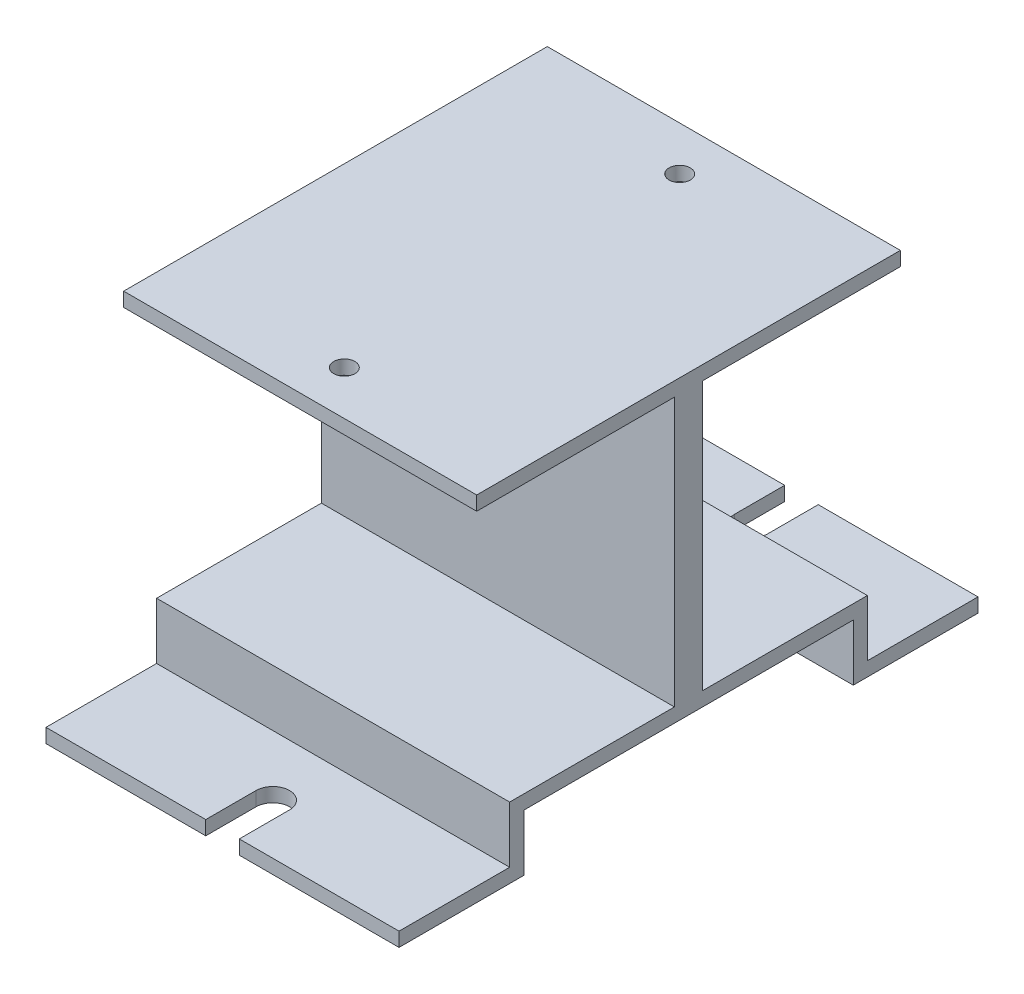
SolidWorks part; units mm, degrees
ref_plane "Front Plane" through (0, 0, 0) normal (0, 0, 1) x (1, 0, 0)
ref_plane "Top Plane" through (0, 0, 0) normal (0, 1, 0) x (1, 0, 0)
ref_plane "Right Plane" through (0, 0, 0) normal (1, 0, 0) x (0, 0, -1)
sketch "Sketch1" plane through (0, 0, 0) normal (1, 0, 0) x (0, 0, -1)
  line L0 (0, 0) -> (0, 42) construction
  line L1 (0, 0) -> (23.3335, 0)
  line L2 (23.3335, 0) -> (23.3335, -8)
  line L3 (23.3335, -8) -> (41, -8)
  line L4 (0, 42) -> (30, 42) construction
  line L5 (0, 42) -> (0, 36.5563) construction
  dimension "D1" = 60
  dimension "D2" = 50
  dimension "D3" = 82
  dimension "D4" = 8
extrude "Extrude-Thin1" add sketch "Sketch1" along normal mid plane 50 thin thin type one direction reverse wall 2
sketch "Sketch2" plane through (0, 0, 0) normal (1, 0, 0) x (0, 0, -1)
  line L0 (0, 0) -> (0, 42) construction
  line L1 (0, 0) -> (0, 42)
  line L2 (0, 42) -> (30, 42) construction
  line L3 (0, 42) -> (30, 42)
extrude "Extrude-Thin2" add sketch "Sketch2" along normal mid plane 50 thin
mirror "Mirror1" of bodies 102
sketch "Sketch3" plane through (0, -6, 0) normal (0, 1, 0) x (1, 0, 0)
  line L0 (0, 33.875) -> (0, 51.5604) construction
  line L1 (-2.375, 33.875) -> (-2.375, 51.5604)
  line L2 (2.375, 33.875) -> (2.375, 51.5604)
  line L3 (0, -27.5) -> (0, 27.5) construction
  line L4 (0, 0) -> (47.2078, 0) construction
  line L5 (0, -33.875) -> (0, -51.5604) construction
  line L6 (-2.375, -33.875) -> (-2.375, -51.5604)
  line L7 (2.375, -33.875) -> (2.375, -51.5604)
  arc A0 (-2.375, 33.875) -> (2.375, 33.875) centre (0, 33.875) ccw
  arc A1 (2.375, 51.5604) -> (-2.375, 51.5604) centre (0, 51.5604) ccw
  arc A2 (-2.375, -33.875) -> (2.375, -33.875) centre (0, -33.875) cw
  arc A3 (2.375, -51.5604) -> (-2.375, -51.5604) centre (0, -51.5604) cw
  point P2 (0, 42.7177)
  point P14 (0, -42.7177)
  dimension "D1" = 4.75
  dimension "D2" = 63
extrude "Cut-Extrude1" cut sketch "Sketch3" against normal blind 10
sketch "Sketch4" plane through (0, 42, 0) normal (0, 1, 0) x (1, 0, 0)
  line L0 (0, 0) -> (0, 30) construction
  line L1 (0, 0) -> (33.6651, 0) construction
  circle A0 centre (0, 23.75) radius 1.5
  circle A1 centre (0, -23.75) radius 1.5
  dimension "D1" = 44.5
  dimension "D2" = 3
extrude "Cut-Extrude2" cut sketch "Sketch4" against normal blind 3
